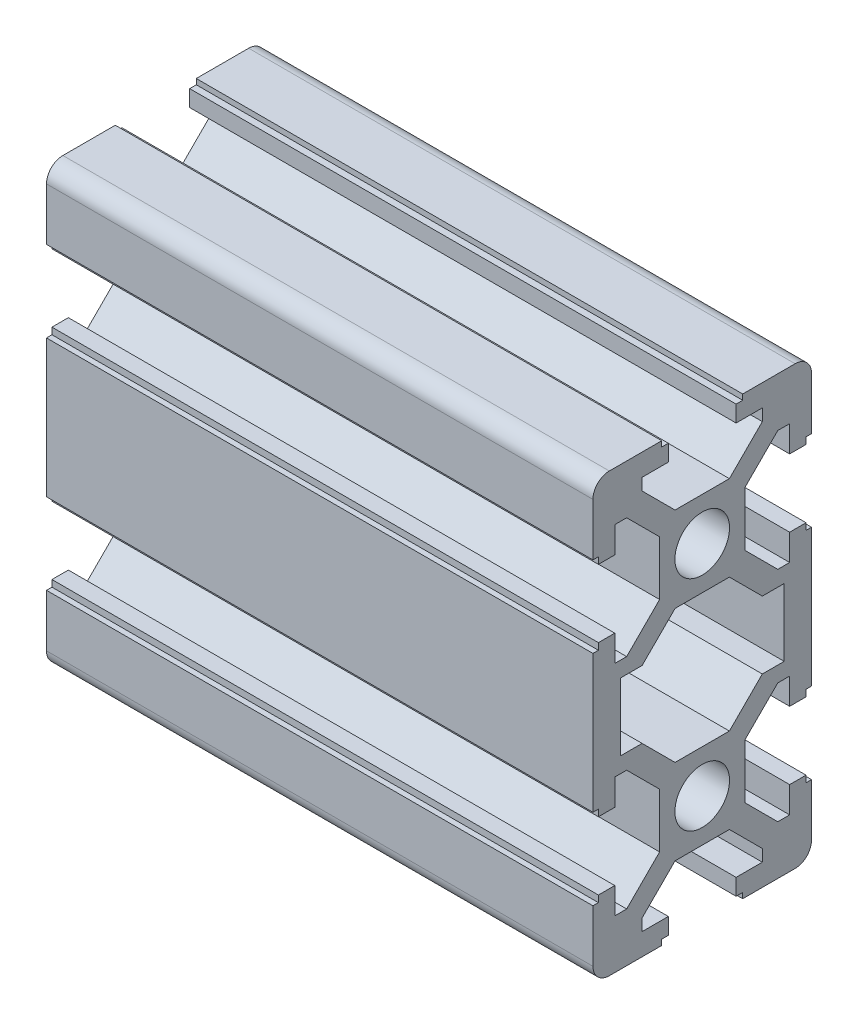
SolidWorks part; units mm, degrees
ref_plane "前视基准面" through (0, 0, 0) normal (0, 0, 1) x (1, 0, 0)
ref_plane "上视基准面" through (0, 0, 0) normal (0, 1, 0) x (1, 0, 0)
ref_plane "右视基准面" through (0, 0, 0) normal (1, 0, 0) x (0, 0, -1)
other "Configuration Table"
ref_plane "基准面1" through (0, 0, 9.923) normal (0, 0, 1) x (1, 0, 0)
sketch "草图1" plane through (0, 0, 9.923) normal (0, 0, 1) x (1, 0, 0)
  line L0 (-1048, 19.9963) -> (-1048, -20.0037)
  line L1 (-1048, -20.0037) -> (0, -20.0037)
  line L2 (0, -20.0037) -> (0, 19.9963)
  line L3 (0, 19.9963) -> (-1048, 19.9963)
extrude "凸台-拉伸1" add sketch "草图1" against normal blind 20
sketch "草图2" plane through (0, 0, 0) normal (1, 0, 0) x (0, 0, -1)
  line L0 (-3.023, 19.9963) -> (-3.023, 17.9963)
  line L1 (-3.023, 17.9963) -> (-5.423, 17.9963)
  line L2 (-5.423, 17.9963) -> (-5.423, 16.9105)
  line L3 (-5.423, 16.9105) -> (-2.4088, 13.8963)
  line L4 (-2.4088, 13.8963) -> (2.5628, 13.8963)
  line L5 (2.5628, 13.8963) -> (5.577, 16.9105)
  line L6 (5.577, 16.9105) -> (5.577, 17.9963)
  line L7 (5.577, 17.9963) -> (3.177, 17.9963)
  line L8 (3.177, 17.9963) -> (3.177, 19.9963)
  line L9 (3.177, 19.9963) -> (-3.023, 19.9963)
extrude "切除-拉伸1" cut sketch "草图2" against normal through all
sketch "草图3" plane through (0, 19.9963, 0) normal (0, 1, 0) x (-1, 0, 0)
  line L0 (9.0173, 3.023) -> (16.9827, 3.023)
  arc A0 (16.9827, 3.023) -> (9.0173, 3.023) centre (13, 0) ccw
extrude "切除-拉伸2" cut sketch "草图3" against normal up to next
sketch "草图4" plane through (-1048, 0, 0) normal (-1, 0, 0) x (0, 0, 1)
  line L0 (3.023, 19.4963) -> (3.628, 19.4963)
  line L1 (3.628, 19.4963) -> (3.628, 19.9963)
  line L2 (3.628, 19.9963) -> (3.023, 19.9963)
  line L3 (3.023, 19.9963) -> (3.023, 19.4963)
extrude "切除-拉伸3" cut sketch "草图4" against normal up to next
sketch "草图5" plane through (0, 0, 0) normal (1, 0, 0) x (0, 0, -1)
  line L0 (-3.023, -20.0037) -> (3.177, -20.0037)
  line L1 (3.177, -20.0037) -> (3.177, -18.0037)
  line L2 (3.177, -18.0037) -> (5.577, -18.0037)
  line L3 (5.577, -18.0037) -> (5.577, -16.9179)
  line L4 (5.577, -16.9179) -> (2.5628, -13.9037)
  line L5 (2.5628, -13.9037) -> (-2.4088, -13.9037)
  line L6 (-2.4088, -13.9037) -> (-5.423, -16.9179)
  line L7 (-5.423, -16.9179) -> (-5.423, -18.0037)
  line L8 (-5.423, -18.0037) -> (-3.023, -18.0037)
  line L9 (-3.023, -18.0037) -> (-3.023, -20.0037)
extrude "切除-拉伸4" cut sketch "草图5" against normal through all
sketch "草图6" plane through (0, -18.0037, 0) normal (0, 1, 0) x (-1, 0, 0)
  line L0 (9.0173, 3.023) -> (16.9827, 3.023)
  arc A0 (16.9827, 3.023) -> (9.0173, 3.023) centre (13, 0) ccw
extrude "切除-拉伸5" cut sketch "草图6" against normal through all
sketch "草图7" plane through (-1048, 0, 0) normal (-1, 0, 0) x (0, 0, 1)
  line L0 (3.023, -20.0037) -> (3.628, -20.0037)
  line L1 (3.628, -20.0037) -> (3.628, -19.5037)
  line L2 (3.628, -19.5037) -> (3.023, -19.5037)
  line L3 (3.023, -19.5037) -> (3.023, -20.0037)
extrude "切除-拉伸6" cut sketch "草图7" against normal up to next
sketch "草图8" plane through (0, -20.0037, 0) normal (0, -1, 0) x (1, 0, 0)
  line L0 (-9.1391, -3.177) -> (-16.8609, -3.177)
  arc A0 (-16.8609, -3.177) -> (-9.1391, -3.177) centre (-13, 0) ccw
extrude "切除-拉伸7" cut sketch "草图8" against normal up to next
sketch "草图9" plane through (-1048, 0, 0) normal (-1, 0, 0) x (0, 0, 1)
  line L0 (-3.177, -20.0037) -> (-3.177, -19.5037)
  line L1 (-3.177, -19.5037) -> (-3.782, -19.5037)
  line L2 (-3.782, -19.5037) -> (-3.782, -20.0037)
  line L3 (-3.782, -20.0037) -> (-3.177, -20.0037)
extrude "切除-拉伸8" cut sketch "草图9" against normal up to next
sketch "草图10" plane through (0, 0, 0) normal (1, 0, 0) x (0, 0, -1)
  line L0 (-3.628, 19.9963) -> (-3.628, 19.4963)
  line L1 (-3.628, 19.4963) -> (-3.023, 19.4963)
  line L2 (-3.023, 19.4963) -> (-3.023, 19.9963)
  line L3 (-3.023, 19.9963) -> (-3.628, 19.9963)
extrude "切除-拉伸9" cut sketch "草图10" against normal up to next
sketch "草图11" plane through (0, 17.9963, 0) normal (0, -1, 0) x (1, 0, 0)
  line L0 (-9.1391, -3.177) -> (-16.8609, -3.177)
  arc A0 (-16.8609, -3.177) -> (-9.1391, -3.177) centre (-13, 0) ccw
extrude "切除-拉伸10" cut sketch "草图11" against normal through all
sketch "草图12" plane through (0, 0, 0) normal (1, 0, 0) x (0, 0, -1)
  line L0 (3.177, 19.9963) -> (3.177, 19.4963)
  line L1 (3.177, 19.4963) -> (3.782, 19.4963)
  line L2 (3.782, 19.4963) -> (3.782, 19.9963)
  line L3 (3.782, 19.9963) -> (3.177, 19.9963)
extrude "切除-拉伸11" cut sketch "草图12" against normal up to next
sketch "草图13" plane through (0, 0, 0) normal (1, 0, 0) x (0, 0, -1)
  line L0 (10.077, 13.7013) -> (9.577, 13.7013)
  line L1 (9.577, 13.7013) -> (9.577, 13.0963)
  line L2 (9.577, 13.0963) -> (8.077, 13.0963)
  line L3 (8.077, 13.0963) -> (8.077, 15.4963)
  line L4 (8.077, 15.4963) -> (6.9912, 15.4963)
  line L5 (6.9912, 15.4963) -> (3.977, 12.4821)
  line L6 (3.977, 12.4821) -> (3.977, 7.5105)
  line L7 (3.977, 7.5105) -> (6.9912, 4.4963)
  line L8 (6.9912, 4.4963) -> (8.077, 4.4963)
  line L9 (8.077, 4.4963) -> (8.077, 6.8963)
  line L10 (8.077, 6.8963) -> (9.577, 6.8963)
  line L11 (9.577, 6.8963) -> (9.577, 6.2913)
  line L12 (9.577, 6.2913) -> (10.077, 6.2913)
  line L13 (10.077, 6.2913) -> (10.077, 13.7013)
extrude "切除-拉伸12" cut sketch "草图13" against normal through all
sketch "草图14" plane through (0, 0, 0) normal (1, 0, 0) x (0, 0, -1)
  line L0 (10.077, -6.2987) -> (9.577, -6.2987)
  line L1 (9.577, -6.2987) -> (9.577, -6.9037)
  line L2 (9.577, -6.9037) -> (8.077, -6.9037)
  line L3 (8.077, -6.9037) -> (8.077, -4.5037)
  line L4 (8.077, -4.5037) -> (6.9912, -4.5037)
  line L5 (6.9912, -4.5037) -> (3.977, -7.5179)
  line L6 (3.977, -7.5179) -> (3.977, -12.4895)
  line L7 (3.977, -12.4895) -> (6.9912, -15.5037)
  line L8 (6.9912, -15.5037) -> (8.077, -15.5037)
  line L9 (8.077, -15.5037) -> (8.077, -13.1037)
  line L10 (8.077, -13.1037) -> (9.577, -13.1037)
  line L11 (9.577, -13.1037) -> (9.577, -13.7087)
  line L12 (9.577, -13.7087) -> (10.077, -13.7087)
  line L13 (10.077, -13.7087) -> (10.077, -6.2987)
extrude "切除-拉伸13" cut sketch "草图14" against normal through all
sketch "草图15" plane through (0, 0, 0) normal (1, 0, 0) x (0, 0, -1)
  line L0 (3.782, -20.0037) -> (3.782, -19.5037)
  line L1 (3.782, -19.5037) -> (3.177, -19.5037)
  line L2 (3.177, -19.5037) -> (3.177, -20.0037)
  line L3 (3.177, -20.0037) -> (3.782, -20.0037)
extrude "切除-拉伸14" cut sketch "草图15" against normal up to next
sketch "草图16" plane through (0, 0, 0) normal (1, 0, 0) x (0, 0, -1)
  line L0 (-3.023, -20.0037) -> (-3.023, -19.5037)
  line L1 (-3.023, -19.5037) -> (-3.628, -19.5037)
  line L2 (-3.628, -19.5037) -> (-3.628, -20.0037)
  line L3 (-3.628, -20.0037) -> (-3.023, -20.0037)
extrude "切除-拉伸15" cut sketch "草图16" against normal up to next
sketch "草图17" plane through (0, 0, 0) normal (1, 0, 0) x (0, 0, -1)
  line L0 (-9.923, -13.7087) -> (-9.423, -13.7087)
  line L1 (-9.423, -13.7087) -> (-9.423, -13.1037)
  line L2 (-9.423, -13.1037) -> (-7.923, -13.1037)
  line L3 (-7.923, -13.1037) -> (-7.923, -15.5037)
  line L4 (-7.923, -15.5037) -> (-6.8372, -15.5037)
  line L5 (-6.8372, -15.5037) -> (-3.823, -12.4895)
  line L6 (-3.823, -12.4895) -> (-3.823, -7.5179)
  line L7 (-3.823, -7.5179) -> (-6.8372, -4.5037)
  line L8 (-6.8372, -4.5037) -> (-7.923, -4.5037)
  line L9 (-7.923, -4.5037) -> (-7.923, -6.9037)
  line L10 (-7.923, -6.9037) -> (-9.423, -6.9037)
  line L11 (-9.423, -6.9037) -> (-9.423, -6.2987)
  line L12 (-9.423, -6.2987) -> (-9.923, -6.2987)
  line L13 (-9.923, -6.2987) -> (-9.923, -13.7087)
extrude "切除-拉伸16" cut sketch "草图17" against normal through all
sketch "草图18" plane through (0, 0, 0) normal (1, 0, 0) x (0, 0, -1)
  line L0 (-9.923, 6.2913) -> (-9.423, 6.2913)
  line L1 (-9.423, 6.2913) -> (-9.423, 6.8963)
  line L2 (-9.423, 6.8963) -> (-7.923, 6.8963)
  line L3 (-7.923, 6.8963) -> (-7.923, 4.4963)
  line L4 (-7.923, 4.4963) -> (-6.8372, 4.4963)
  line L5 (-6.8372, 4.4963) -> (-3.823, 7.5105)
  line L6 (-3.823, 7.5105) -> (-3.823, 12.4821)
  line L7 (-3.823, 12.4821) -> (-6.8372, 15.4963)
  line L8 (-6.8372, 15.4963) -> (-7.923, 15.4963)
  line L9 (-7.923, 15.4963) -> (-7.923, 13.0963)
  line L10 (-7.923, 13.0963) -> (-9.423, 13.0963)
  line L11 (-9.423, 13.0963) -> (-9.423, 13.7013)
  line L12 (-9.423, 13.7013) -> (-9.923, 13.7013)
  line L13 (-9.923, 13.7013) -> (-9.923, 6.2913)
extrude "切除-拉伸17" cut sketch "草图18" against normal through all
sketch "草图19" plane through (-1048, 0, 0) normal (-1, 0, 0) x (0, 0, 1)
  line L0 (-3.782, 19.9963) -> (-3.782, 19.4963)
  line L1 (-3.782, 19.4963) -> (-3.177, 19.4963)
  line L2 (-3.177, 19.4963) -> (-3.177, 19.9963)
  line L3 (-3.177, 19.9963) -> (-3.782, 19.9963)
extrude "切除-拉伸18" cut sketch "草图19" against normal up to next
sketch "草图20" plane through (-1048, 0, 0) normal (-1, 0, 0) x (0, 0, 1)
  line L0 (2.4088, -3.0895) -> (7.423, -3.0895)
  line L1 (7.423, -3.0895) -> (7.423, 3.0821)
  line L2 (7.423, 3.0821) -> (2.4088, 3.0821)
  line L3 (2.4088, 3.0821) -> (2.4088, 6.0963)
  line L4 (2.4088, 6.0963) -> (-2.5628, 6.0963)
  line L5 (-2.5628, 6.0963) -> (-2.5628, 3.0821)
  line L6 (-2.5628, 3.0821) -> (-7.577, 3.0821)
  line L7 (-7.577, 3.0821) -> (-7.577, -3.0895)
  line L8 (-7.577, -3.0895) -> (-2.5628, -3.0895)
  line L9 (-2.5628, -3.0895) -> (-2.5628, -6.1037)
  line L10 (-2.5628, -6.1037) -> (2.4088, -6.1037)
  line L11 (2.4088, -6.1037) -> (2.4088, -3.0895)
extrude "切除-拉伸19" cut sketch "草图20" against normal through all
draft "拔模1" type of draft neutral plane draft angle 45 faces to draft 2 face at (-524, -4.5966, 2.4088) face at (-524, -4.5966, -2.5628) neutral plane through (0, -6.1037, -2.5628) neutral plane normal (0, 1, 0) parameters "D1"=45
draft "拔模2" type of draft neutral plane draft angle 45 faces to draft 2 face at (-524, 4.5892, -2.5628) face at (-524, 4.5892, 2.4088) neutral plane through (0, 6.0963, 2.4088) neutral plane normal (0, -1, 0) parameters "D1"=45
ref_plane "基准面2" through (0, 0, 0) normal (0, 0, -1) x (-1, 0, 0)
sketch "草图21" plane through (0, 0, 0) normal (0, 0, -1) x (-1, 0, 0)
  line L0 (8, 10.9963) -> (13, 10.9963)
  line L1 (13, 10.9963) -> (13, 16.4875)
  line L2 (13, 16.4875) -> (8, 16.4875)
  line L3 (8, 16.4875) -> (8, 10.9963)
  line L4 (13, 10.9963) -> (13, 16.4875) construction
revolve "切除-旋转1" cut sketch "草图21" angle 360 about L4
sketch "草图22" plane through (0, 0, 0) normal (0, 0, 1) x (1, 0, 0)
  line L0 (-8, -10.9963) -> (-13, -10.9963)
  line L1 (-13, -10.9963) -> (-13, -16.4949)
  line L2 (-13, -16.4949) -> (-8, -16.4949)
  line L3 (-8, -16.4949) -> (-8, -10.9963)
  line L4 (-13, -10.9963) -> (-13, -16.4949) construction
revolve "切除-旋转2" cut sketch "草图22" angle 360 about L4
hole_wizard "Ø5.0 (5) 直径孔1" positions "草图24" profile "草图23" hole size "Ø5.0" standard "ANSI Metric"
sketch "草图24" plane through (0, 0, 0) normal (1, 0, 0) x (0, 0, -1)
  point P0 (0.077, 9.9963)
sketch "草图23" plane through (0, 9.9963, -0.077) normal (0, 1, 0) x (0, 0, -1)
  line L0 (0, 0) -> (0, 1048)
  line L1 (0, 1048) -> (2.5, 1048)
  line L2 (2.5, 1048) -> (2.5, 0)
  line L5 (2.5, 0) -> (0, 0)
  line L11 (0, -6.35) -> (0, 107.95) construction
  dimension "通孔孔直径" = 5
  dimension "通孔孔深度" = 1048
hole_wizard "Ø5.0 (5) 直径孔2" positions "草图26" profile "草图25" hole size "Ø5.0" standard "ANSI Metric"
sketch "草图26" plane through (-1048, 0, 0) normal (-1, 0, 0) x (0, 0, 1)
  point P0 (-0.077, -10.0037)
sketch "草图25" plane through (-1048, -10.0037, -0.077) normal (0, 1, 0) x (0, 0, 1)
  line L0 (0, 0) -> (0, 1048)
  line L1 (0, 1048) -> (2.5, 1048)
  line L2 (2.5, 1048) -> (2.5, 0)
  line L5 (2.5, 0) -> (0, 0)
  line L11 (0, -6.35) -> (0, 107.95) construction
  dimension "通孔孔直径" = 5
  dimension "通孔孔深度" = 1048
fillet "圆角1" radius 1.5 4 edges at (-524, 19.9963, -10.077) (-524, -20.0037, -10.077) (-524, 19.9963, 9.923) (-524, -20.0037, 9.923)
sketch "草图27" plane through (0, 0, 0) normal (1, 0, 0) x (0, 0, -1)
  line L1 (-12.5, -22.5) -> (12.5, -22.5)
  line L2 (-12.5, -22.5) -> (-12.5, 22.5)
  line L3 (-12.5, 22.5) -> (12.5, 22.5)
  line L4 (12.5, -22.5) -> (12.5, 22.5)
  line L5 (-12.5, -22.5) -> (12.5, 22.5) construction
  line L6 (-12.5, 22.5) -> (12.5, -22.5) construction
  point P0 (0, 0)
  dimension "D1" = 45
  dimension "D2" = 25
extrude "切除-拉伸21" cut sketch "草图27" against normal blind 496.5
sketch "草图28" plane through (0, 0, 0) normal (1, 0, 0) x (0, 0, -1)
  line L4 (-12.5, -22.5) -> (12.5, -22.5)
  line L5 (12.5, -22.5) -> (12.5, 22.5)
  line L6 (12.5, 22.5) -> (-12.5, 22.5)
  line L7 (-12.5, 22.5) -> (-12.5, -22.5)
  line L8 (-12.5, -22.5) -> (12.5, -22.5)
  line L9 (12.5, -22.5) -> (12.5, 22.5)
  line L10 (12.5, 22.5) -> (-12.5, 22.5)
  line L11 (-12.5, 22.5) -> (-12.5, -22.5)
  dimension "D1" = 0
extrude "切除-拉伸22" cut sketch "草图28" along normal blind 501.5 from surface at -1048 starting at face at (-1048, -10.0037, 2.423)
